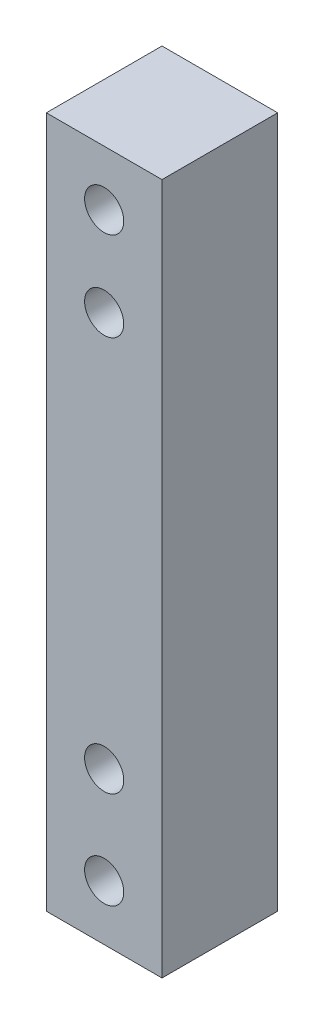
SolidWorks part; units mm, degrees
ref_plane "Front Plane" through (0, 0, 0) normal (0, 0, 1) x (1, 0, 0)
ref_plane "Top Plane" through (0, 0, 0) normal (0, 1, 0) x (1, 0, 0)
ref_plane "Right Plane" through (0, 0, 0) normal (1, 0, 0) x (0, 0, -1)
sketch "Sketch1" plane through (0, 0, 0) normal (0, 0, 1) x (1, 0, 0)
  line L8 (-20.5, -128.1) -> (-33.5, -128.1)
  line L9 (-33.5, -128.1) -> (-33.5, -205.8)
  line L10 (-33.5, -205.8) -> (-20.5, -205.8)
  line L11 (-20.5, -205.8) -> (-20.5, -128.1)
  circle A4 centre (-27, -134.3) radius 2.2
  circle A5 centre (-27, -144.3) radius 2.2
  circle A6 centre (-27, -199.6) radius 2.2
  circle A7 centre (-27, -188.7) radius 2.2
extrude "Boss-Extrude1" add sketch "Sketch1" against normal blind 13
